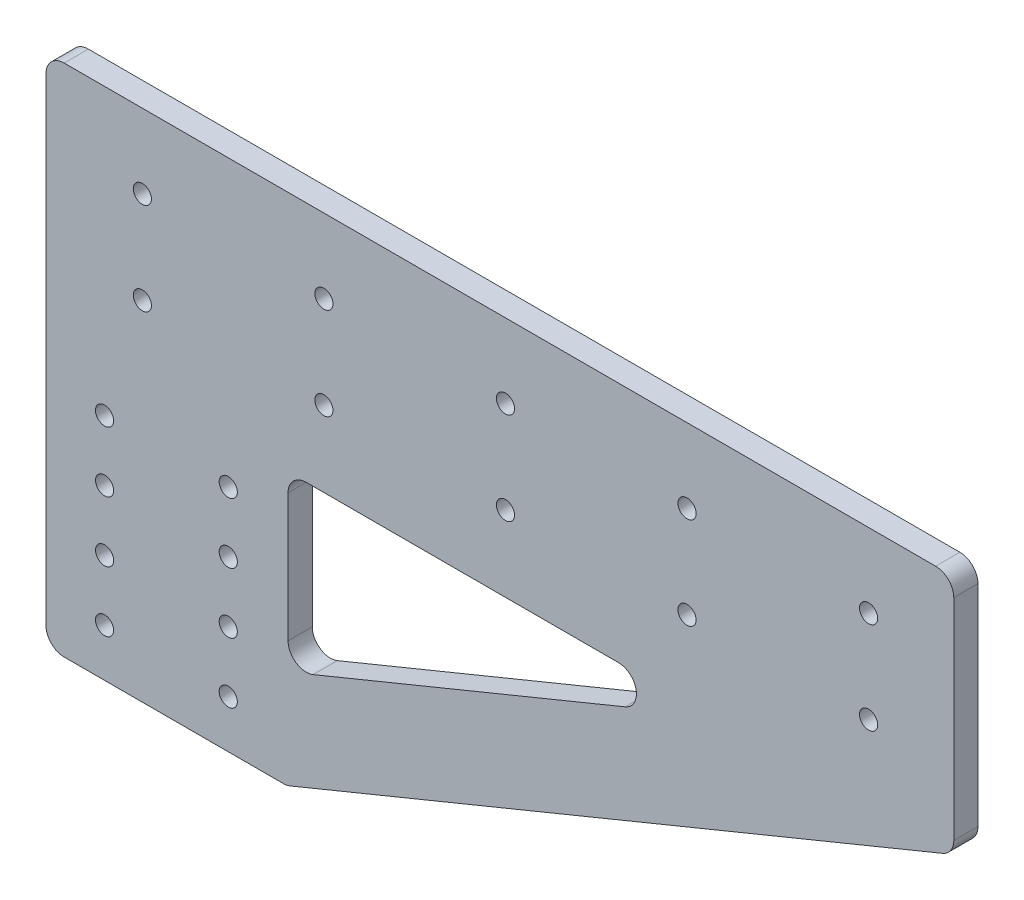
SolidWorks part; units mm, degrees
ref_plane "前视基准面" through (0, 0, 0) normal (0, 0, 1) x (1, 0, 0)
ref_plane "上视基准面" through (0, 0, 0) normal (0, 1, 0) x (1, 0, 0)
ref_plane "右视基准面" through (0, 0, 0) normal (1, 0, 0) x (0, 0, -1)
sketch "草图1" plane through (0, 0, 0) normal (0, 0, 1) x (1, 0, 0)
  line L1 (-75, -42.5) -> (75, -42.5)
  line L2 (-75, -42.5) -> (-75, 42.5)
  line L3 (-75, 42.5) -> (75, 42.5)
  line L4 (75, -42.5) -> (75, 42.5)
  line L5 (-75, -42.5) -> (75, 42.5) construction
  line L6 (-75, 42.5) -> (75, -42.5) construction
  point P0 (0, 0)
  dimension "D1" = 150
  dimension "D2" = 85
extrude "凸台-拉伸1" add sketch "草图1" along normal blind 4
sketch "草图2" plane through (0, 0, 0) normal (0, 0, -1) x (-1, 0, 0)
  line L0 (35.205, -42.5) -> (-75, 2.7404)
  line L3 (75, -42.5) -> (-75, -42.5) construction
  line L4 (-75, -42.5) -> (-75, 42.5) construction
  line L5 (-75, 2.7404) -> (-77.4979, -0.1313)
  line L6 (-77.4979, -0.1313) -> (-84.3905, -55.5058)
  line L7 (-84.3905, -55.5058) -> (-64.8344, -59.1159)
  line L8 (-64.8344, -59.1159) -> (35.205, -42.5)
extrude "切除-拉伸1" cut sketch "草图2" against normal blind 10
sketch "草图3" plane through (0, 0, 0) normal (0, 0, -1) x (-1, 0, 0)
  line L0 (-75, 22.6202) -> (89.5259, 22.6202) construction
  line L1 (-75, 2.7404) -> (-75, 42.5) construction
  line L2 (55.1025, -42.5) -> (55.1025, 88.2907) construction
  line L3 (75, -42.5) -> (35.205, -42.5) construction
  line L4 (55.1025, 87.7404) -> (55.1025, -43.0504) construction
  circle A0 centre (-60.9211, 30.2358) radius 1.5
  circle A1 centre (-30.9211, 30.2358) radius 1.5
  circle A2 centre (-0.9211, 30.2358) radius 1.5
  circle A3 centre (29.0789, 30.2358) radius 1.5
  circle A4 centre (59.0789, 30.2358) radius 1.5
  circle A5 centre (59.0789, 15.0046) radius 1.5
  circle A6 centre (29.0789, 15.0046) radius 1.5
  circle A7 centre (-0.9211, 15.0046) radius 1.5
  circle A8 centre (-30.9211, 15.0046) radius 1.5
  circle A9 centre (-60.9211, 15.0046) radius 1.5
  circle A10 centre (44.8838, -4.6002) radius 1.5
  circle A11 centre (44.8838, -14.6002) radius 1.5
  circle A12 centre (44.8838, -24.6002) radius 1.5
  circle A13 centre (44.8838, -34.6002) radius 1.5
  circle A14 centre (65.3212, -34.6002) radius 1.5
  circle A15 centre (65.3212, -24.6002) radius 1.5
  circle A16 centre (65.3212, -14.6002) radius 1.5
  circle A17 centre (65.3212, -4.6002) radius 1.5
  dimension "D1" = 3
  dimension "D3" = 3
  dimension "D2" = 5
  dimension "D4" = 4
extrude "切除-拉伸2" cut sketch "草图3" against normal blind 10
sketch "草图4" plane through (0, 0, 0) normal (0, 0, -1) x (-1, 0, 0)
  line L0 (-34.7718, 2.5) -> (35, -26.1421)
  line L1 (-316, 2.5) -> (75, 2.5) construction
  line L2 (35, 2.5) -> (35, -95.5) construction
  line L3 (35.205, -42.5) -> (-75, 2.7404) construction
  line L4 (-34.7718, 2.5) -> (35, 2.5)
  line L5 (35, 2.5) -> (35, -26.1421)
extrude "切除-拉伸3" cut sketch "草图4" against normal blind 10
fillet "圆角1" radius 3 8 edges at (-35.205, -42.5, 2) (75, 2.7404, 2) (75, 42.5, 2) (-75, 42.5, 2) (-75, -42.5, 2) (-35, 2.5, 2) (-35, -26.1421, 2) (34.7718, 2.5, 2)
